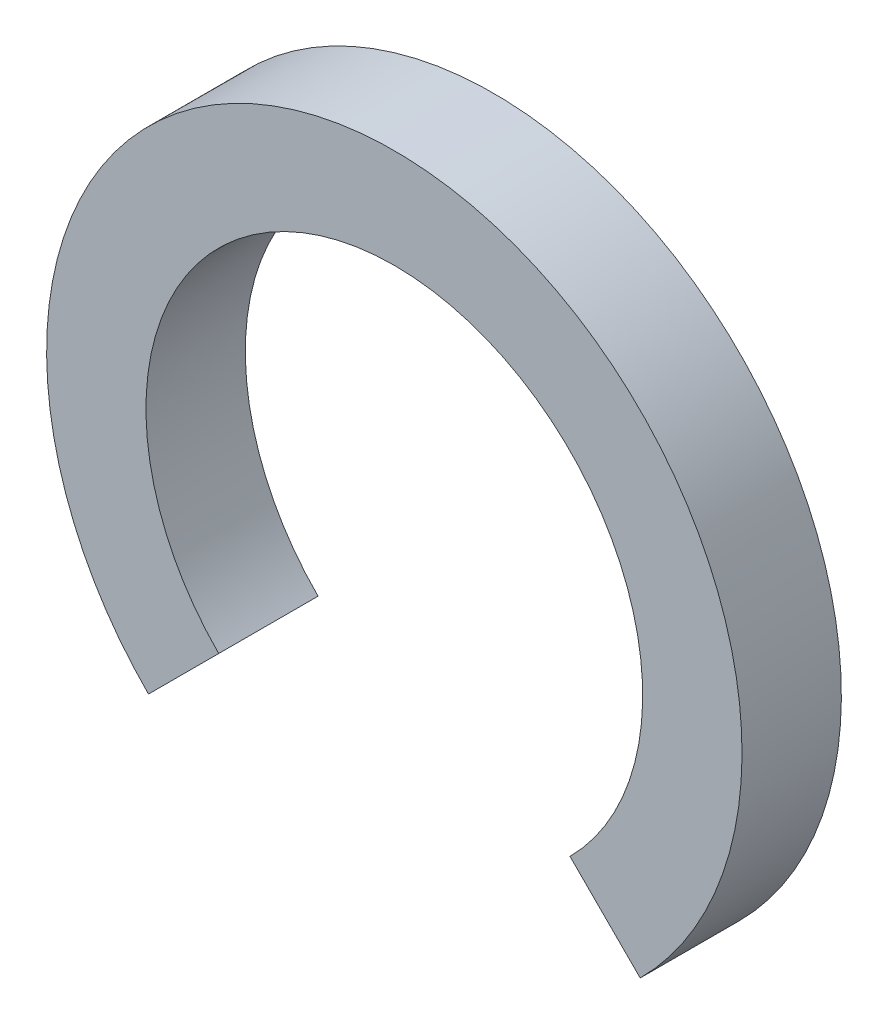
SolidWorks part; units mm, degrees
ref_plane "Plan de face" through (0, 0, 0) normal (0, 0, 1) x (1, 0, 0)
ref_plane "Plan de dessus" through (0, 0, 0) normal (0, 1, 0) x (1, 0, 0)
ref_plane "Plan de droite" through (0, 0, 0) normal (1, 0, 0) x (0, 0, -1)
sketch "Esquisse1" plane through (0, 0, 0) normal (0, 0, 1) x (1, 0, 0)
  line L0 (0, 4.8404) -> (0, -5.195) construction
  line L1 (1.7678, -1.7678) -> (2.4749, -2.4749)
  line L2 (-1.7678, -1.7678) -> (-2.4749, -2.4749)
  line L3 (0, 3.5) -> (0, 2.5)
  arc A0 (2.4749, -2.4749) -> (-2.4749, -2.4749) centre (0, 0) ccw
  arc A1 (1.7678, -1.7678) -> (-1.7678, -1.7678) centre (0, 0) ccw
  dimension "D1" = 2.5
  dimension "D2" = 3.5
extrude "Boss.-Extru.1" add sketch "Esquisse1" along normal blind 1 contours A0 L2 A1 L1
